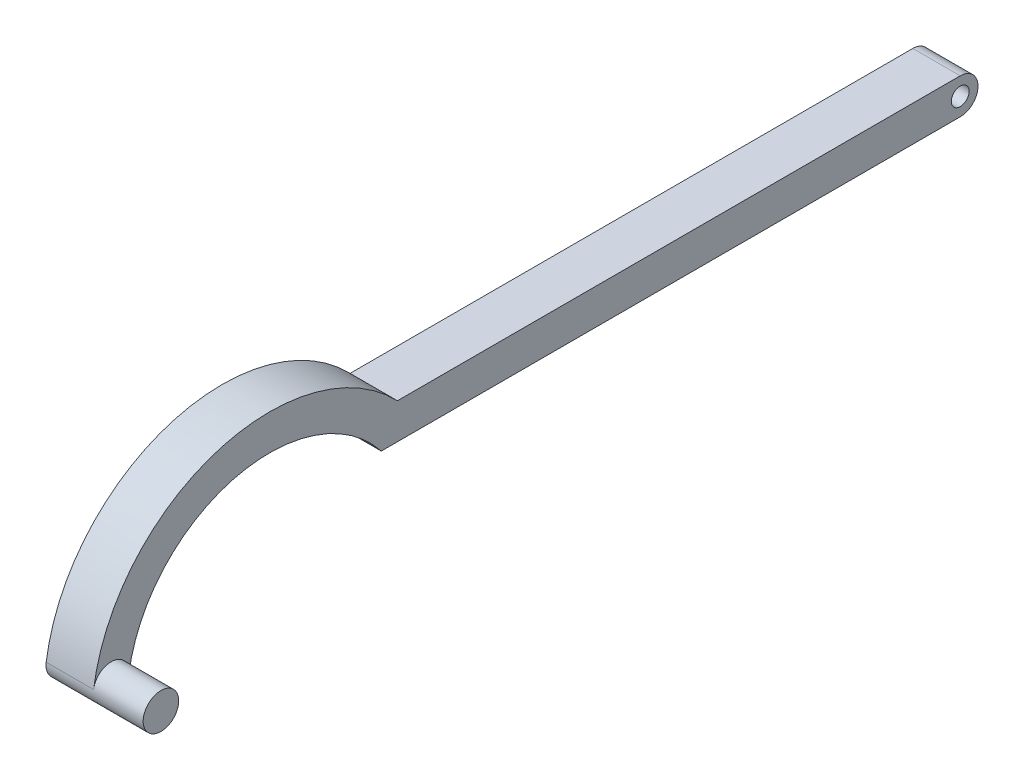
SolidWorks part; units mm, degrees
ref_plane "Front Plane" through (0, 0, 0) normal (0, 0, 1) x (1, 0, 0)
ref_plane "Top Plane" through (0, 0, 0) normal (0, 1, 0) x (1, 0, 0)
ref_plane "Right Plane" through (0, 0, 0) normal (1, 0, 0) x (0, 0, -1)
sketch "Sketch1" plane through (0, 0, 0) normal (1, 0, 0) x (0, 0, -1)
  line L0 (0, 0) -> (71.6589, 7) construction
  line L2 (71.6589, 8.5) -> (24.1589, 8.5)
  line L4 (71.6589, 5.5) -> (22.7989, 5.5)
  arc A0 (-1.4848, 0.2127) -> (1.4848, -0.2127) centre (0, 0) ccw
  arc A1 (71.6589, 5.5) -> (71.6589, 8.5) centre (71.6589, 7) ccw
  circle A4 centre (0, 0) radius 1.5 construction
  circle A5 centre (71.6589, 7) radius 0.75
  arc A6 (1.4848, -0.2127) -> (22.7989, 5.5) centre (13.3636, -1.9144) cw
  arc A7 (-1.4848, 0.2127) -> (24.1589, 8.5) centre (13.3636, -1.9144) cw
  dimension "D1" = 72
  dimension "D2" = 3
  dimension "D5" = 3
  dimension "D6" = 1.5
  dimension "D4" = 12
  dimension "D3" = 7
  dimension "D7" = 47.5
extrude "Boss-Extrude1" add sketch "Sketch1" along normal blind 4
sketch "Sketch2" plane through (4, 0, 0) normal (1, 0, 0) x (0, 0, -1)
  circle A0 centre (0, 0) radius 1.5
extrude "Boss-Extrude2" add sketch "Sketch2" along normal blind 4.2
